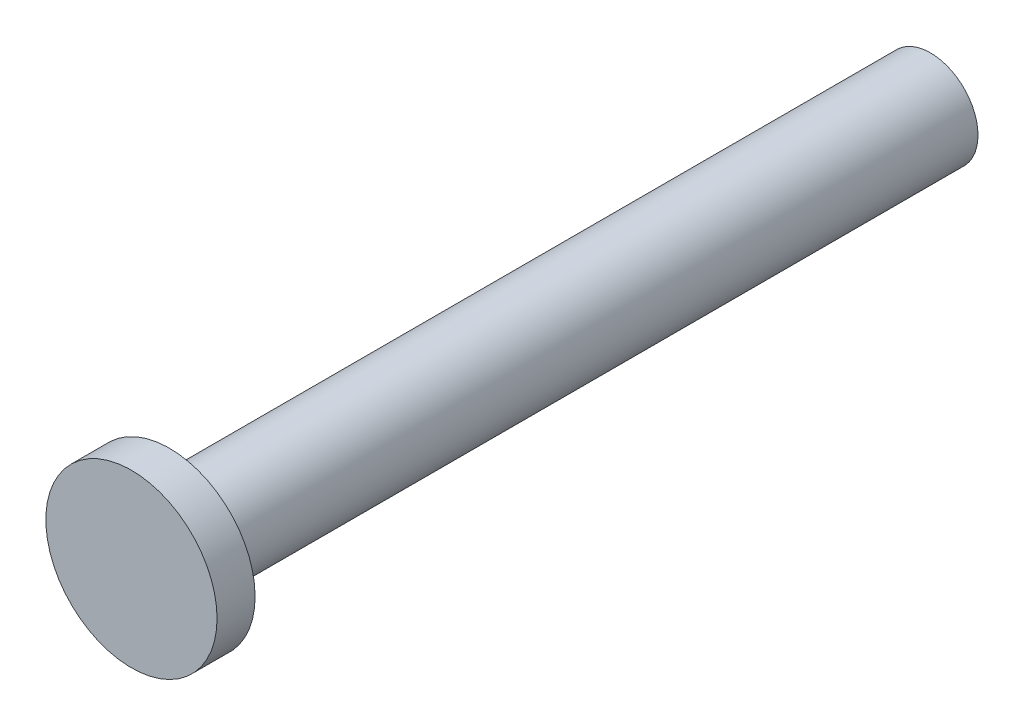
SolidWorks part; units mm, degrees
ref_plane "Front Plane" through (0, 0, 0) normal (0, 0, 1) x (1, 0, 0)
ref_plane "Top Plane" through (0, 0, 0) normal (0, 1, 0) x (1, 0, 0)
ref_plane "Right Plane" through (0, 0, 0) normal (1, 0, 0) x (0, 0, -1)
sketch "Sketch1" plane through (0, 0, 0) normal (0, 0, 1) x (1, 0, 0)
  circle A0 centre (0, 0) radius 2.5
  dimension "D1" = 5
extrude "Boss-Extrude1" add sketch "Sketch1" along normal blind 40
sketch "Sketch2" plane through (0, 0, 40) normal (0, 0, 1) x (1, 0, 0)
  circle A0 centre (0, 0) radius 4.5
  circle A1 centre (0, 0) radius 2.5
  circle A2 centre (0, 0) radius 2.5 construction
  dimension "D1" = 0
  dimension "D2" = 2
extrude "Boss-Extrude2" add sketch "Sketch2" along normal blind 2
